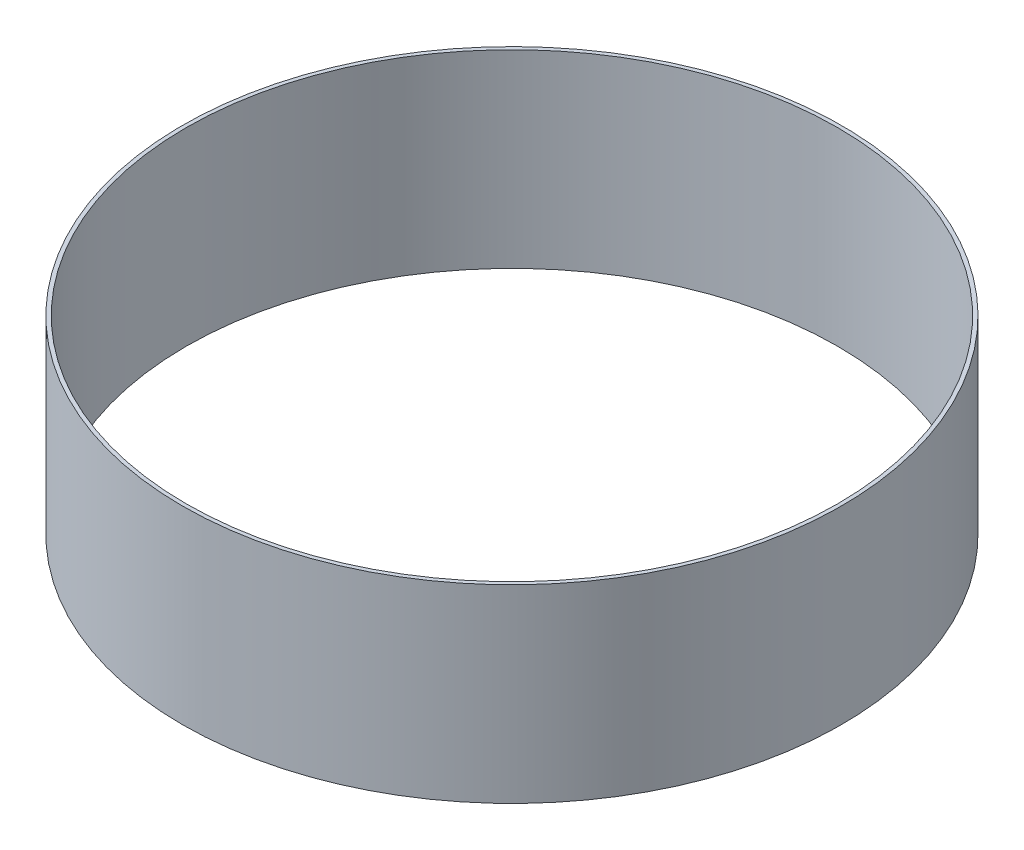
SolidWorks part; units mm, degrees
ref_plane "Front Plane" through (0, 0, 0) normal (0, 0, 1) x (1, 0, 0)
ref_plane "Top Plane" through (0, 0, 0) normal (0, 1, 0) x (1, 0, 0)
ref_plane "Right Plane" through (0, 0, 0) normal (1, 0, 0) x (0, 0, -1)
sketch "Sketch1" plane through (0, 0, 0) normal (0, 0, 1) x (1, 0, 0)
  line L0 (0, 91.7468) -> (0, -48.0019)
  line L1 (131.064, 76.2) -> (132.588, 76.2)
  line L2 (131.064, 76.2) -> (131.064, 0)
  line L3 (131.064, 0) -> (132.588, 0)
  line L4 (132.588, 76.2) -> (132.588, 0)
  point P8 (0, 21.8724)
  dimension "D1" = 1.524
  dimension "D2" = 76.2
  dimension "D3" = 132.588
revolve "Revolve1" add sketch "Sketch1" angle 360 about L0
